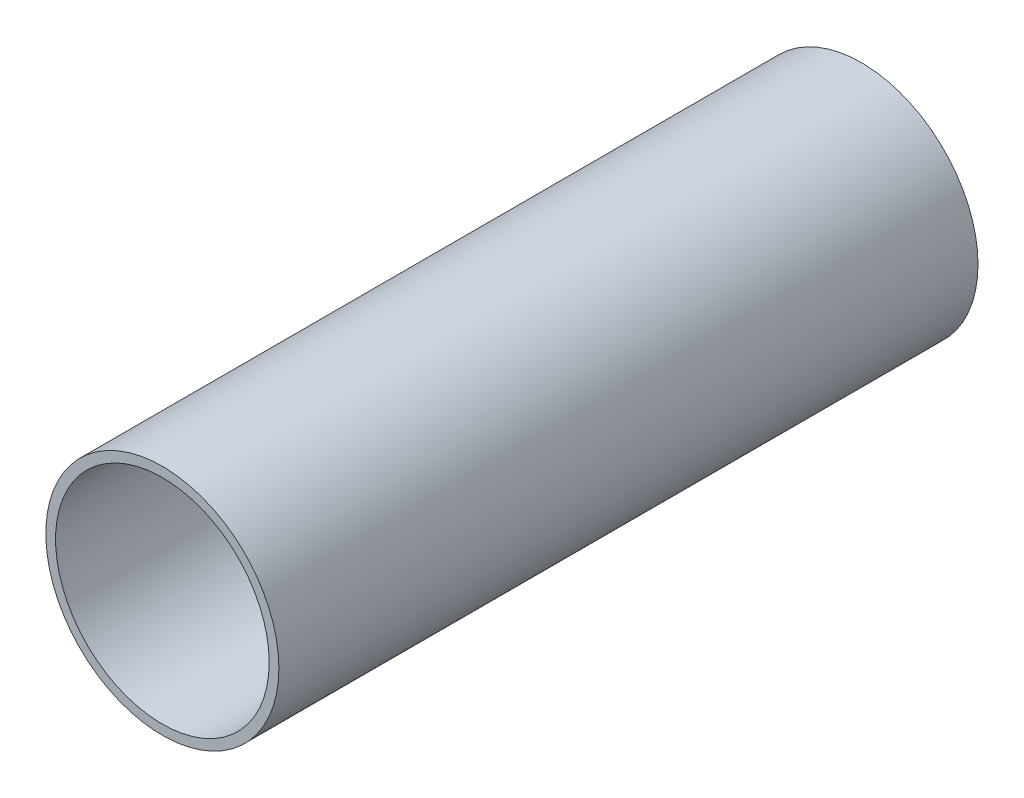
SolidWorks part; units mm, degrees
ref_plane "Front Plane" through (0, 0, 0) normal (0, 0, 1) x (1, 0, 0)
ref_plane "Top Plane" through (0, 0, 0) normal (0, 1, 0) x (1, 0, 0)
ref_plane "Right Plane" through (0, 0, 0) normal (1, 0, 0) x (0, 0, -1)
sketch "Sketch3" plane through (0, 0, 0) normal (0, 0, 1) x (1, 0, 0)
  circle A0 centre (0, 0) radius 38.1
  circle A1 centre (0, 0) radius 34.925
  dimension "D1" = 76.2
  dimension "D2" = 69.85
extrude "Boss-Extrude2" add sketch "Sketch3" along normal blind 228.6
sketch "Sketch5" plane through (0, 0, 0) normal (0, 1, 0) x (1, 0, 0)
  circle A0 centre (-3.1084, -79.1683) radius 6.35
  circle A1 centre (-3.1084, -155.3683) radius 6.35
  point P4 (0, 0)
  dimension "D2" = 12.7
  dimension "D1" = 76.2
extrude "Cut-Extrude3" cut sketch "Sketch5" against normal through all
